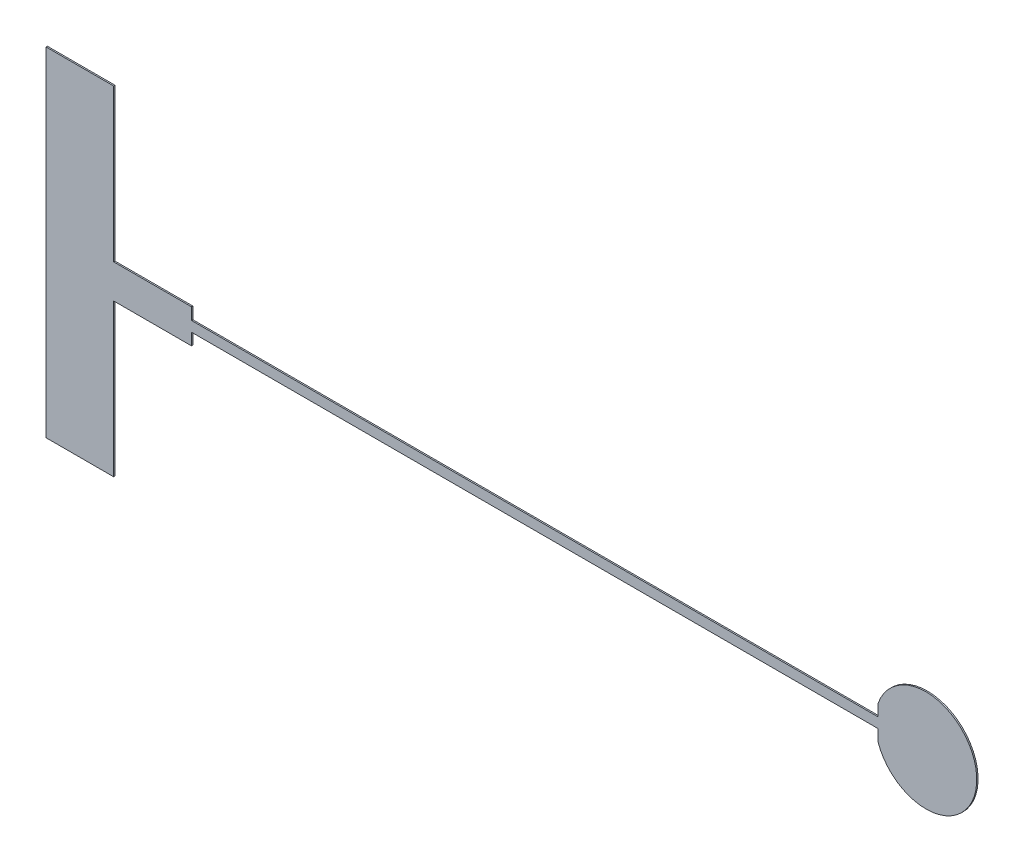
SolidWorks part; units mm, degrees
ref_plane "Front Plane" through (0, 0, 0) normal (0, 0, 1) x (1, 0, 0)
ref_plane "Top Plane" through (0, 0, 0) normal (0, 1, 0) x (1, 0, 0)
ref_plane "Right Plane" through (0, 0, 0) normal (1, 0, 0) x (0, 0, -1)
sketch "Sketch1" plane through (0, 0, 0) normal (0, 0, 1) x (1, 0, 0)
  line L0 (1000, 250) -> (5000, 250)
  line L1 (-1000, 2500) -> (1000, 2500)
  line L2 (-1000, 2500) -> (-1000, -2500)
  line L3 (-1000, -2500) -> (1000, -2500)
  line L4 (1000, 2500) -> (1000, 250)
  line L5 (-1000, 2500) -> (1000, -2500) construction
  line L6 (-1000, -2500) -> (1000, 2500) construction
  line L9 (1000, -250) -> (5000, -250)
  line L10 (5000, 250) -> (5000, 125)
  line L11 (-3000, 250) -> (5000, -250) construction
  line L12 (-3000, -250) -> (5000, 250) construction
  line L13 (5000, 125) -> (9000, 125)
  line L15 (5000, -125) -> (9000, -125)
  line L16 (9000, 125) -> (9000, 100)
  line L17 (1000, 125) -> (9000, -125) construction
  line L18 (1000, -125) -> (9000, 125) construction
  line L19 (9000, 100) -> (11256.6966, 100)
  line L21 (9000, -100) -> (11256.6966, -100)
  line L23 (6000, 100) -> (12000, -100) construction
  line L24 (6000, -100) -> (12000, 100) construction
  line L25 (1000, -250) -> (1000, -2500)
  line L26 (5000, -125) -> (5000, -250)
  line L27 (9000, -100) -> (9000, -125)
  arc A0 (11256.6966, -100) -> (11256.6966, 100) centre (12000, 0) ccw
  point P0 (0, 0)
  point P6 (1000, 0)
  point P11 (5000, 0)
  point P16 (9000, 0)
  dimension "D9" = 1500
  dimension "D1" = 2000
  dimension "D2" = 5000
  dimension "D3" = 500
  dimension "D4" = 4000
  dimension "D5" = 250
  dimension "D6" = 4000
  dimension "D7" = 200
extrude "Boss-Extrude1" add sketch "Sketch1" against normal blind 20
sketch "Sketch2" plane through (0, 0, 0) normal (0, 0, 1) x (1, 0, 0)
  line L0 (0, -11) -> (0, 11) construction
  line L1 (1000, 2500) -> (0, 2500)
  line L2 (1000, 2500) -> (1000, 250)
  line L3 (1000, 250) -> (0, 250)
  line L4 (0, 2500) -> (0, 250)
  line L5 (1000, -2500) -> (0, -2500)
  line L6 (1000, -2500) -> (1000, -250)
  line L7 (1000, -250) -> (0, -250)
  line L8 (0, -2500) -> (0, -250)
  dimension "D1" = 1000
  dimension "D2" = 2250
extrude "Cut-Extrude1" cut sketch "Sketch2" against normal through all
sketch "Sketch3" plane through (0, 0, 0) normal (0, 0, 1) x (1, 0, 0)
  line L0 (0, 0) -> (1098.3807, 0) construction
  line L1 (11, 0) -> (-11, 0) construction
  line L2 (5000, 250) -> (0, 250) construction
  line L3 (1500, 250) -> (3250, 250)
  line L4 (1500, 250) -> (1500, 200)
  line L5 (1500, 200) -> (3250, 200)
  line L7 (0, -250) -> (5000, -250) construction
  line L8 (1500, -250) -> (3250, -250)
  line L9 (1500, -250) -> (1500, -200)
  line L10 (1500, -200) -> (3250, -200)
  line L12 (0, -11) -> (0, 11) construction
  line L13 (3250, 200) -> (3250, 150)
  line L14 (3250, 250) -> (5000, 250)
  line L16 (3250, 150) -> (5000, 150)
  line L17 (5000, 250) -> (5000, 150)
  line L18 (3250, -250) -> (5000, -250)
  line L19 (3250, -200) -> (3250, -150)
  line L20 (3250, -150) -> (5000, -150)
  line L21 (5000, -250) -> (5000, -150)
  point P17 (1500, 225)
  dimension "D1" = 1098.3807
  dimension "D2" = 1750
  dimension "D3" = 50
  dimension "D4" = 1750
  dimension "D5" = 50
  dimension "D6" = 1500
  dimension "D7" = 1500
  dimension "D8" = 100
  dimension "D9" = 100
  dimension "D10" = 1750
  dimension "D11" = 1750
extrude "Cut-Extrude4" cut sketch "Sketch3" against normal through all contours L8 L18 L21 L20 L19 L10 L9
mirror "Mirror1" about plane through (0, 0, 0) normal (0, 1, 0) of "Cut-Extrude4"
sketch "Sketch5" plane through (0, 0, 0) normal (0, 0, 1) x (1, 0, 0)
  line L0 (0, -11) -> (0, 11) construction
  line L1 (0, -250) -> (11500, -250)
  line L2 (0, -250) -> (0, 250)
  line L3 (0, 250) -> (11500, 250)
  line L4 (11500, -250) -> (11500, 250)
  line L5 (0, -250) -> (1500, -250) construction
  dimension "D1" = 500
  dimension "D2" = 11500
extrude "Boss-Extrude2" add sketch "Sketch5" against normal blind 20
sketch "Sketch7" plane through (0, 0, 0) normal (0, 0, 1) x (1, 0, 0)
  line L0 (11292.8932, 250) -> (0, 250) construction
  line L1 (1150, 250) -> (11292.8932, 250)
  line L2 (1150, 250) -> (1150, 150)
  line L3 (1150, 150) -> (11292.8932, 150)
  line L4 (11292.8932, 250) -> (11292.8932, 150)
  line L5 (0, 2500) -> (0, 250) construction
  dimension "D1" = 1150
  dimension "D2" = 0
  dimension "D3" = 100
extrude "Cut-Extrude5" cut sketch "Sketch7" against normal through all
mirror "Mirror2" about plane through (0, 0, 0) normal (0, 1, 0) of "Cut-Extrude5"
sketch "Sketch8" plane through (0, 0, 0) normal (0, 0, 1) x (1, 0, 0)
  line L0 (11292.8932, 150) -> (11292.8932, 250) construction
  line L1 (1150, 150) -> (11292.8932, 150)
  line L2 (1150, 150) -> (1150, 75)
  line L3 (1150, 75) -> (11292.8932, 75)
  line L4 (11292.8932, 150) -> (11292.8932, 75)
  dimension "D1" = 0
  dimension "D2" = 75
extrude "Cut-Extrude6" cut sketch "Sketch8" against normal through all
mirror "Mirror3" about plane through (0, 0, 0) normal (0, 1, 0) of "Cut-Extrude6"
